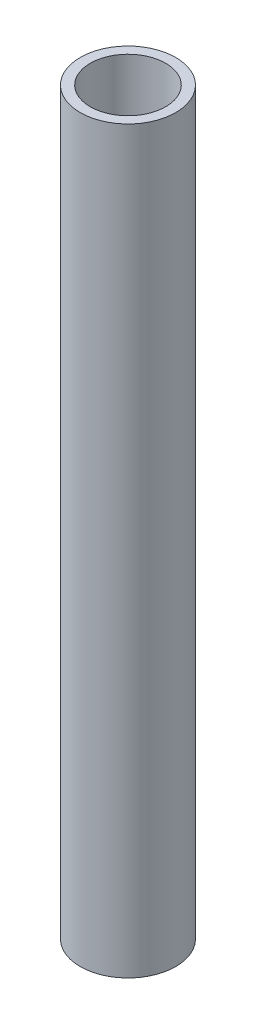
SolidWorks part; units mm, degrees
ref_plane "Front Plane" through (0, 0, 0) normal (0, 0, 1) x (1, 0, 0)
ref_plane "Top Plane" through (0, 0, 0) normal (0, 1, 0) x (1, 0, 0)
ref_plane "Right Plane" through (0, 0, 0) normal (1, 0, 0) x (0, 0, -1)
sketch "Sketch1" plane through (0, 0, 0) normal (0, 1, 0) x (1, 0, 0)
  circle A0 centre (0, 0) radius 24.13
  circle A1 centre (0, 0) radius 19.05
  dimension "D1" = 48.26
  dimension "D2" = 38.1
extrude "Boss-Extrude1" add sketch "Sketch1" along normal mid plane 373.634
